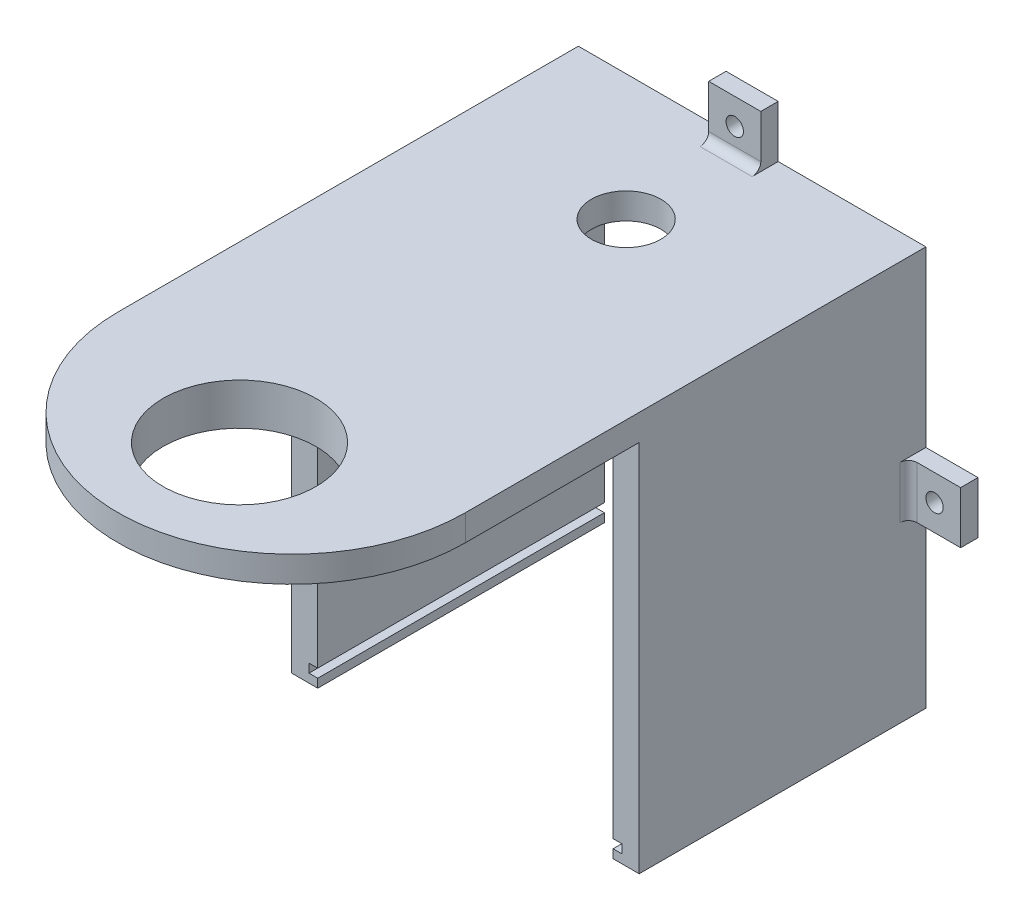
SolidWorks part; units mm, degrees
ref_plane "Front Plane" through (0, 0, 0) normal (0, 0, 1) x (1, 0, 0)
ref_plane "Top Plane" through (0, 0, 0) normal (0, 1, 0) x (1, 0, 0)
ref_plane "Right Plane" through (0, 0, 0) normal (1, 0, 0) x (0, 0, -1)
sketch "Sketch1" plane through (0, 0, 0) normal (0, 0, 1) x (1, 0, 0)
  line L1 (21.59, -25.4) -> (-21.59, -25.4)
  line L2 (21.59, -25.4) -> (21.59, 25.4)
  line L3 (21.59, 25.4) -> (-21.59, 25.4)
  line L4 (-21.59, -25.4) -> (-21.59, 25.4)
  line L5 (21.59, -25.4) -> (-21.59, 25.4) construction
  line L6 (21.59, 25.4) -> (-21.59, -25.4) construction
  point P0 (0, 0)
  dimension "D1" = 50.8
  dimension "D2" = 43.18
extrude "Extrude-Thin1" add sketch "Sketch1" along normal blind 41.91 thin thin type one direction wall 3.81
sketch "Sketch2" plane through (0, 29.21, 0) normal (0, 1, 0) x (1, 0, 0)
  line L0 (-25.4, -20.955) -> (-4.54, -20.955) construction
  line L1 (-25.4, -41.91) -> (-25.4, 0) construction
  circle A0 centre (0, -18.415) radius 5.08
  dimension "D1" = 10.16
  dimension "D2" = 2.54
extrude "Cut-Extrude1" cut sketch "Sketch2" against normal blind 5.08
sketch "Sketch3" plane through (0, -29.21, 0) normal (0, -1, 0) x (1, 0, 0)
  line L0 (-25.4, 41.91) -> (25.4, 41.91) construction
  line L1 (-21.59, 41.91) -> (21.59, 41.91)
  line L2 (-21.59, 41.91) -> (-21.59, 0)
  line L3 (-21.59, 0) -> (21.59, 0)
  line L4 (21.59, 41.91) -> (21.59, 0)
  line L5 (-25.4, 0) -> (25.4, 0) construction
  line L6 (25.4, 41.91) -> (25.4, 0) construction
  line L7 (-25.4, 41.91) -> (-25.4, 0) construction
  dimension "D1" = 3.81
  dimension "D2" = 3.81
extrude "Cut-Extrude2" cut sketch "Sketch3" against normal blind 5.08
sketch "Sketch4" plane through (0, 0, 0) normal (0, 0, -1) x (-1, 0, 0)
  line L0 (25.4, 29.21) -> (25.4, -29.21) construction
  line L1 (33.02, -3.81) -> (25.4, -3.81)
  line L2 (33.02, -3.81) -> (33.02, 3.81)
  line L3 (33.02, 3.81) -> (25.4, 3.81)
  line L4 (25.4, -3.81) -> (25.4, 3.81)
  line L5 (33.02, -3.81) -> (25.4, 3.81) construction
  line L6 (33.02, 3.81) -> (25.4, -3.81) construction
  line L7 (-25.4, -29.21) -> (-25.4, 29.21) construction
  line L8 (-33.02, 3.81) -> (-25.4, 3.81)
  line L9 (-33.02, 3.81) -> (-33.02, -3.81)
  line L10 (-33.02, -3.81) -> (-25.4, -3.81)
  line L11 (-25.4, 3.81) -> (-25.4, -3.81)
  line L12 (-33.02, 3.81) -> (-25.4, -3.81) construction
  line L13 (-33.02, -3.81) -> (-25.4, 3.81) construction
  line L14 (-25.4, 29.21) -> (25.4, 29.21) construction
  line L15 (3.81, 36.83) -> (-3.81, 36.83)
  line L16 (3.81, 36.83) -> (3.81, 29.21)
  line L17 (3.81, 29.21) -> (-3.81, 29.21)
  line L18 (-3.81, 36.83) -> (-3.81, 29.21)
  line L19 (3.81, 36.83) -> (-3.81, 29.21) construction
  line L20 (3.81, 29.21) -> (-3.81, 36.83) construction
  circle A0 centre (-29.21, 0) radius 1.27
  circle A1 centre (0, 33.02) radius 1.27
  circle A2 centre (29.21, 0) radius 1.27
  point P0 (29.21, 0)
  point P9 (-29.21, 0)
  point P15 (0, 33.02)
  dimension "D2" = 2.54
  dimension "D1" = 7.62
extrude "Boss-Extrude1" add sketch "Sketch4" against normal blind 2.54
ref_plane "Plane1" through (0, 0, 0) normal (-1, 0, 0) x (0, 0, 1)
sketch "Sketch5" plane through (21.59, 0, 0) normal (-1, 0, 0) x (0, 0, 1)
  line L0 (0, -3.81) -> (0, -29.21) construction
  line L1 (0, -27.94) -> (41.91, -27.94)
  line L2 (0, -27.94) -> (0, -26.67)
  line L3 (0, -26.67) -> (41.91, -26.67)
  line L4 (41.91, -27.94) -> (41.91, -26.67)
  line L5 (41.91, 29.21) -> (41.91, -29.21) construction
  line L6 (41.91, -29.21) -> (0, -29.21) construction
  dimension "D1" = 1.27
  dimension "D2" = 1.27
extrude "Cut-Extrude3" cut sketch "Sketch5" against normal blind 1.27
mirror "Mirror1" about plane through (0, 0, 0) normal (-1, 0, 0) of "Cut-Extrude3"
sketch "Sketch6" plane through (0, 29.21, 0) normal (0, 1, 0) x (1, 0, 0)
  line L1 (25.4, -67.31) -> (-25.4, -67.31) construction
  line L2 (25.4, -67.31) -> (25.4, -41.91)
  line L3 (25.4, -41.91) -> (-25.4, -41.91)
  line L4 (-25.4, -67.31) -> (-25.4, -41.91)
  line L5 (25.4, -67.31) -> (-25.4, -41.91) construction
  line L6 (25.4, -41.91) -> (-25.4, -67.31) construction
  arc A0 (-25.4, -67.31) -> (25.4, -67.31) centre (0, -67.31) ccw
  circle A2 centre (0, -74.93) radius 11.176
  point P0 (0, -54.61)
  dimension "D2" = 22.352
  dimension "D3" = 7.62
  dimension "D1" = 25.4
extrude "Boss-Extrude2" add sketch "Sketch6" against normal blind 3.81
fillet "Fillet2" radius 1.27 3 edges at (-25.4, 0, 2.54) (0, 29.21, 2.54) (25.4, 0, 2.54)
sketch "Sketch7" plane through (0, 25.4, 0) normal (0, -1, 0) x (1, 0, 0)
  circle A0 centre (0, 74.93) radius 11.176
  circle A1 centre (0, 74.93) radius 14.986
  circle A2 centre (0, 74.93) radius 11.176 construction
  dimension "D1" = 3.81
extrude "Boss-Extrude3" add sketch "Sketch7" along normal blind 2.286
